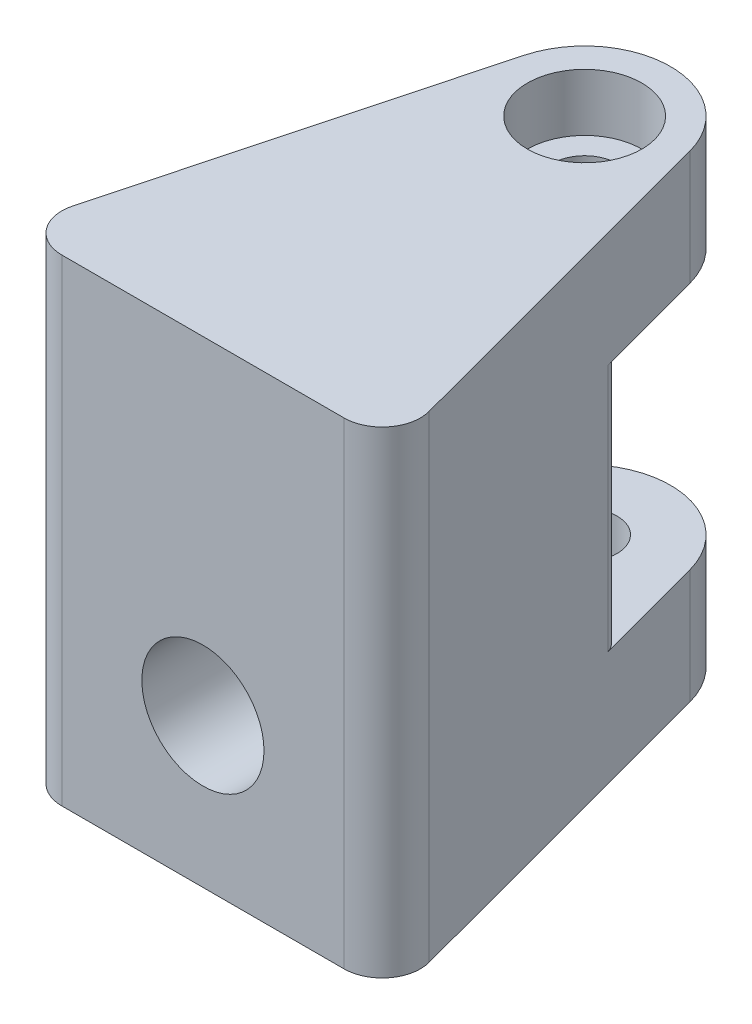
SolidWorks part; units mm, degrees
ref_plane "Alzado" through (0, 0, 0) normal (0, 0, 1) x (1, 0, 0)
ref_plane "Planta" through (0, 0, 0) normal (0, 1, 0) x (1, 0, 0)
ref_plane "Vista lateral" through (0, 0, 0) normal (1, 0, 0) x (0, 0, -1)
sketch "Croquis1" plane through (0, 0, 0) normal (0, 1, 0) x (1, 0, 0)
  line L0 (-4.3476, 1.1613) -> (-10, -20)
  line L1 (-10, -20) -> (10, -20)
  line L2 (10, -20) -> (4.3476, 1.1613)
  line L3 (0, -55) -> (0, 55) construction
  arc A0 (4.3476, 1.1613) -> (-4.3476, 1.1613) centre (0, 0) ccw
  point P1 (0, -20)
  dimension "D1" = 4.5
  dimension "D2" = 20
  dimension "D3" = 20
extrude "Saliente-Extruir1" add sketch "Croquis1" along normal blind 25
sketch "Croquis2" plane through (0, 0, 20) normal (0, 0, 1) x (1, 0, 0)
  line L0 (0, -13.475) -> (0, 13.475) construction
  line L1 (11, 0) -> (-11, 0) construction
  circle A0 centre (0, 7.8) radius 3.2
  dimension "D1" = 6.4
  dimension "D2" = 7.8
extrude "Cortar-Extruir1" cut sketch "Croquis2" against normal blind 12
fillet "Redondeo1" radius 2 2 edges at (10, 12.5, 20) (-10, 12.5, 20)
sketch "Croquis3" plane through (0, 25, 0) normal (0, 1, 0) x (1, 0, 0)
  circle A0 centre (0, 0) radius 1.7
  dimension "D1" = 3.4
extrude "Cortar-Extruir2" cut sketch "Croquis3" against normal through all
sketch "Croquis4" plane through (0, 0, 0) normal (0, 1, 0) x (1, 0, 0)
  circle A0 centre (0, 0) radius 6
  dimension "D1" = 12
extrude "Cortar-Extruir3" cut sketch "Croquis4" along normal offset from surface (13 mm away) 6 from offset 6 up to face at (0, 25, 1.7)
sketch "Croquis6" plane through (0, 0, 0) normal (0, 1, 0) x (1, 0, 0)
  line L0 (0, -13.475) -> (0, 13.475) construction
  line L1 (0, -3.4641) -> (3, -1.7321)
  line L2 (3, -1.7321) -> (3, 1.7321)
  line L3 (3, 1.7321) -> (0, 3.4641)
  line L4 (0, 3.4641) -> (-3, 1.7321)
  line L5 (-3, 1.7321) -> (-3, -1.7321)
  line L6 (-3, -1.7321) -> (0, -3.4641)
  circle A0 centre (0, 0) radius 3 construction
  dimension "D1" = 6
extrude "Cortar-Extruir5" cut sketch "Croquis6" along normal blind 2.4
sketch "Croquis7" plane through (0, 25, 0) normal (0, 1, 0) x (1, 0, 0)
  circle A0 centre (0, 0) radius 3
  dimension "D1" = 6
extrude "Cortar-Extruir6" cut sketch "Croquis7" against normal blind 3
fillet "Redondeo2" radius 1 2 edges at (5.3717, 12.5, 2.6729) (-5.3717, 12.5, 2.6729)
